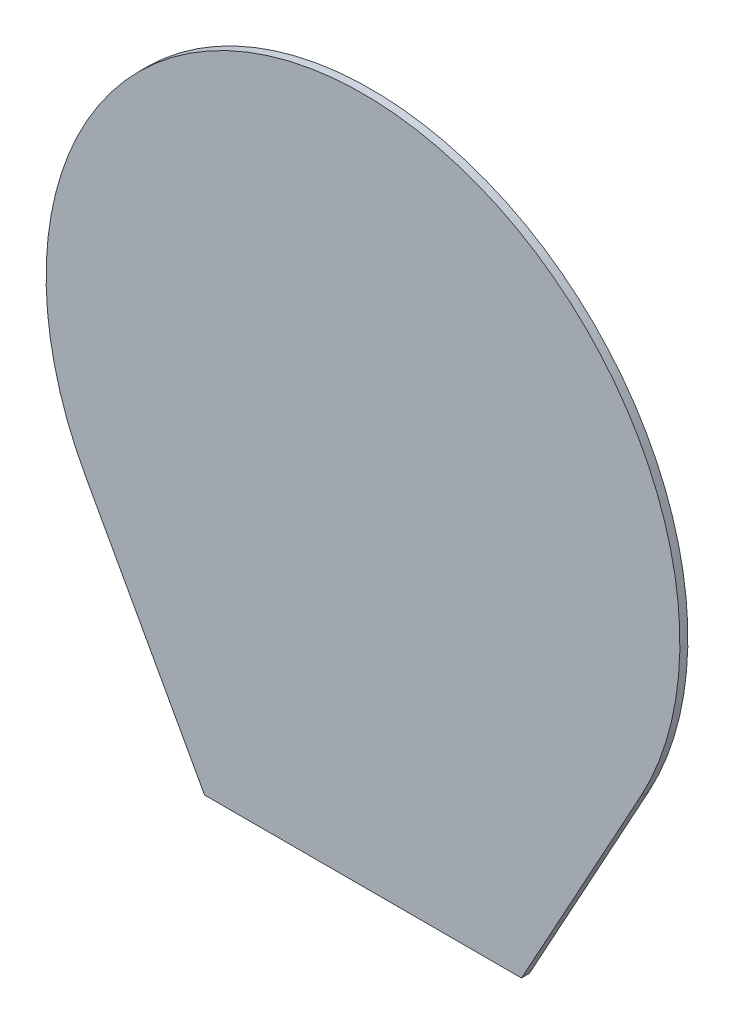
SolidWorks part; units mm, degrees
ref_plane "Plano frontal" through (0, 0, 0) normal (0, 0, 1) x (1, 0, 0)
ref_plane "Plano superior" through (0, 0, 0) normal (0, 1, 0) x (1, 0, 0)
ref_plane "Plano direito" through (0, 0, 0) normal (1, 0, 0) x (0, 0, -1)
sketch "Sketch1" plane through (0, 0, 0) normal (0, 0, 1) x (1, 0, 0)
  line L0 (-15, -35) -> (-7.5, -35)
  line L1 (-15, -35) -> (15, -35)
  line L4 (-15, -35) -> (-7.5, -35)
  line L7 (15, -35) -> (26.2929, -14.4459)
  line L16 (-15, -35) -> (-26.2929, -14.4459)
  arc A2 (26.2929, -14.4459) -> (-26.2929, -14.4459) centre (0, 0) ccw
  point P5 (0, 0)
  point P10 (0, -35)
  dimension "D3" = 60
  dimension "D5" = 30
  dimension "D6" = 7.5
extrude "Boss-Extrude1" add sketch "Sketch1" along normal blind 0.7544
